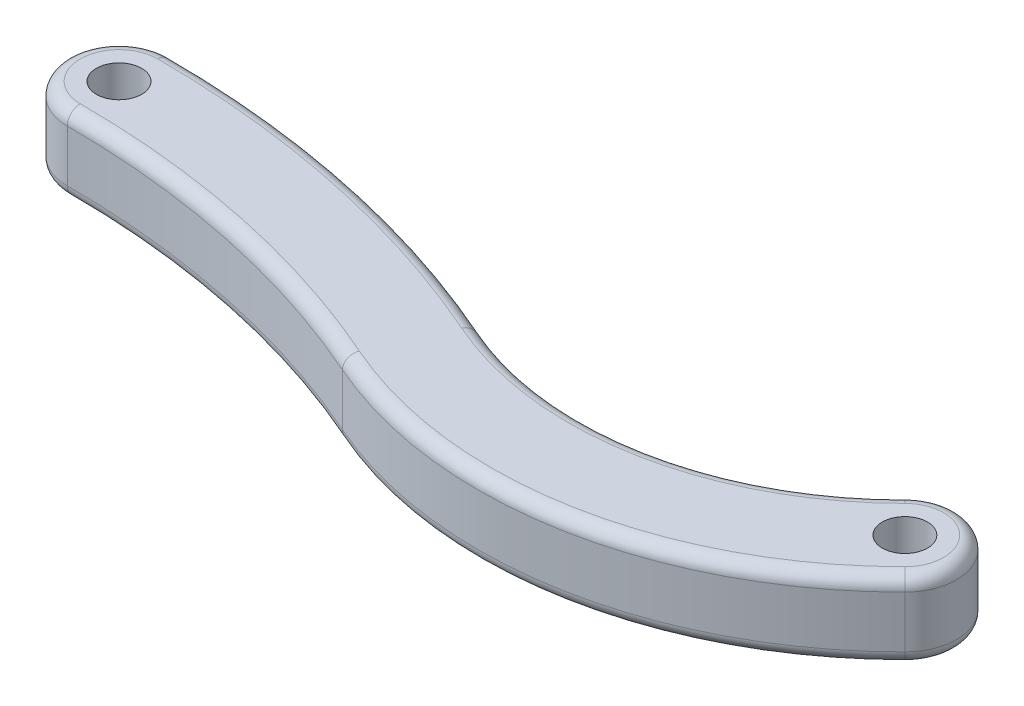
SolidWorks part; units mm, degrees
ref_plane "Front Plane" through (0, 0, 0) normal (0, 0, 1) x (1, 0, 0)
ref_plane "Top Plane" through (0, 0, 0) normal (0, 1, 0) x (1, 0, 0)
ref_plane "Right Plane" through (0, 0, 0) normal (1, 0, 0) x (0, 0, -1)
sketch "Sketch1" plane through (0, 0, 0) normal (0, 1, 0) x (1, 0, 0)
  line L0 (-30.4, 0) -> (30.4, 0) construction
  line L3 (30.2031, 0.1969) -> (1.0567, 29.3433) construction
  circle A2 centre (-30.4, 0) radius 1.75
  circle A3 centre (30.4, 0) radius 1.75
  arc A4 (-30.4, 4) -> (-30.4, -4) centre (-30.4, 0) ccw
  arc A5 (33.2284, -2.8284) -> (27.5716, 2.8284) centre (30.4, 0) ccw
  arc A7 (-0.1976, -2.3666) -> (27.5716, 2.8284) centre (9.8939, 20.5061) ccw
  arc A9 (-3.4269, -9.6859) -> (33.2284, -2.8284) centre (9.8939, 20.5061) ccw
  arc A10 (-30.4, 4) -> (-0.1976, -2.3666) centre (-30.4, -70.8213) cw
  arc A11 (-30.4, -4) -> (-3.4269, -9.6859) centre (-30.4, -70.8213) cw
  dimension "D1" = 3.5
  dimension "D8" = 33
  dimension "D2" = 60.8
  dimension "D3" = 30.4
  dimension "D4" = 8
  dimension "D6" = 8
  dimension "D5" = 45
  dimension "D7" = 8
extrude "Boss-Extrude1" add sketch "Sketch1" along normal blind 6
fillet "Fillet1" radius 1 12 edges at (33.2284, 6, -2.8284) (15.9623, 6, 11.9312) (-16.6171, 6, 5.4369) (-34.4, 6, 0) (-14.9669, 6, -2.391) (33.2284, 0, -2.8284) (15.9623, 0, 11.9312) (-16.6171, 0, 5.4369) (-34.4, 0, 0) (-14.9669, 0, -2.391) (14.4911, 6, 4.0676) (14.4911, 0, 4.0676)
equation "\"D3@Sketch1\"=\"D2@Sketch1\"/2"
